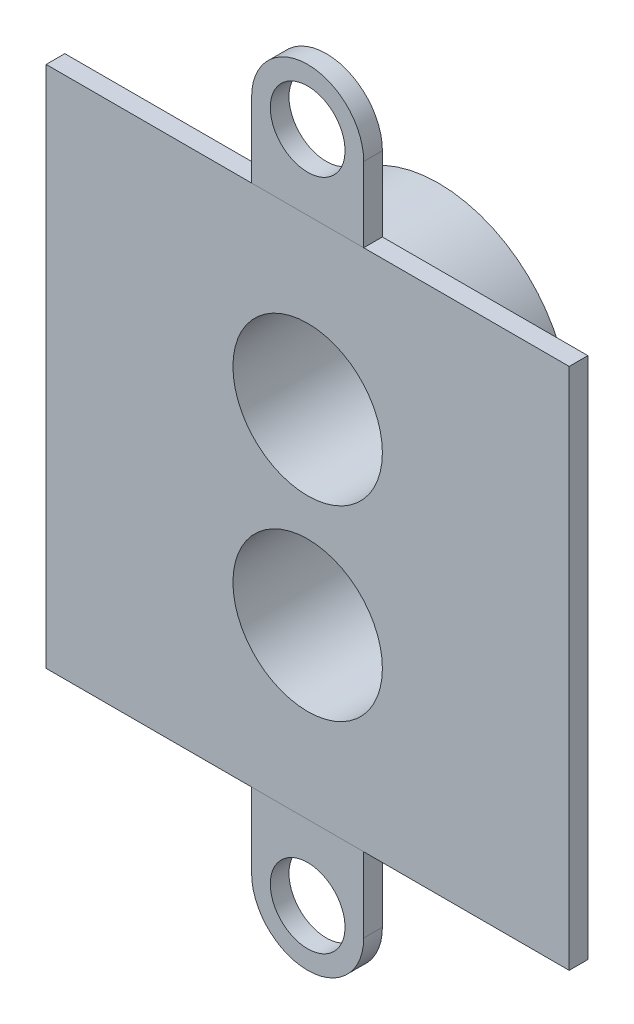
SolidWorks part; units mm, degrees
ref_plane "前视基准面" through (0, 0, 0) normal (0, 0, 1) x (1, 0, 0)
ref_plane "上视基准面" through (0, 0, 0) normal (0, 1, 0) x (1, 0, 0)
ref_plane "右视基准面" through (0, 0, 0) normal (1, 0, 0) x (0, 0, -1)
sketch "草图2" plane through (0, 0, 0) normal (0, 0, 1) x (1, 0, 0)
  line L5 (7, -7) -> (-7, -7)
  line L6 (7, -7) -> (7, 7)
  line L7 (7, 7) -> (-7, 7)
  line L8 (-7, -7) -> (-7, 7)
  line L9 (7, -7) -> (-7, 7) construction
  line L10 (7, 7) -> (-7, -7) construction
  circle A0 centre (0, 2.5) radius 2
  circle A1 centre (0, -2.5) radius 2
  point P0 (0, 0)
  dimension "D3" = 4
  dimension "D4" = 4
  dimension "D1" = 14
  dimension "D2" = 14
  dimension "D5" = 4.5
  dimension "D6" = 4.5
extrude "凸台-拉伸1" add sketch "草图2" along normal blind 0.5 contours L8 L5 L6 L7 A1 A0
sketch "草图3" plane through (0, -7, 0) normal (0, -1, 0) x (1, 0, 0)
  line L0 (7, 0) -> (-7, 0) construction
  line L1 (-1.5, 0.5) -> (1.5, 0.5)
  line L2 (-1.5, 0.5) -> (-1.5, 0)
  line L3 (-1.5, 0) -> (1.5, 0)
  line L4 (1.5, 0.5) -> (1.5, 0)
  line L5 (-1.5, 0.5) -> (1.5, 0) construction
  line L6 (-1.5, 0) -> (1.5, 0.5) construction
  line L7 (7, 0.5) -> (-7, 0.5) construction
  point P0 (0, 0.25)
  point P5 (0, 0)
  point P6 (0, 0)
  point P7 (0, 0)
  point P11 (0, 0)
  dimension "D1" = 3
extrude "凸台-拉伸2" add sketch "草图3" along normal blind 3.5 separate body
sketch "草图4" plane through (0, 0, 0) normal (0, 0, -1) x (-1, 0, 0)
  line L0 (1.5, -10.5) -> (1.5, -7) construction
  line L1 (1.5, -10.5) -> (-1.5, -10.5) construction
  line L2 (-1.5, -10.5) -> (-1.5, -7) construction
  line L3 (1.5, -9) -> (1.5, -10.5)
  line L4 (1.5, -10.5) -> (-1.5, -10.5)
  line L5 (-1.5, -10.5) -> (-1.5, -9)
  circle A0 centre (0, -9) radius 1.5
  line M3 (-1.5, -7) -> (-1.5, -10.5)
  line M4 (-1.5, -10.5) -> (1.5, -10.5)
  line M5 (1.5, -10.5) -> (1.5, -7)
extrude "切除-拉伸1" cut sketch "草图4" against normal blind 4 contours A0 L4 M5 | A0 M3 M4
sketch "草图5" plane through (0, 0, 0) normal (0, 0, -1) x (-1, 0, 0)
  circle A0 centre (0, -9) radius 1
  dimension "D1" = 2
  dimension "D2" = 9
extrude "切除-拉伸2" cut sketch "草图5" against normal blind 4
mirror "镜向7" about plane through (0, 0, 0) normal (0, 1, 0) of bodies 109
sketch "草图8" plane through (0, 0, 0) normal (0, 0, -1) x (-1, 0, 0)
  circle A0 centre (0, -2.5) radius 2 construction
  circle A1 centre (0, 2.5) radius 2 construction
  circle A2 centre (0, -2.5) radius 2
  circle A3 centre (0, 2.5) radius 2
  arc A6 (2.4495, 0) -> (-2.4495, 0) centre (0, 2.5) ccw
  arc A7 (-2.4495, 0) -> (2.4495, 0) centre (0, -2.5) ccw
  circle A9 centre (0, -2.5) radius 3.5 construction
  circle A10 centre (0, 2.5) radius 3.5 construction
  point P9 (3.5, 3)
  point P10 (3.5, -3)
  dimension "D1" = 1.5
extrude "凸台-拉伸4" add sketch "草图8" along normal blind 3 contours A6 A7
